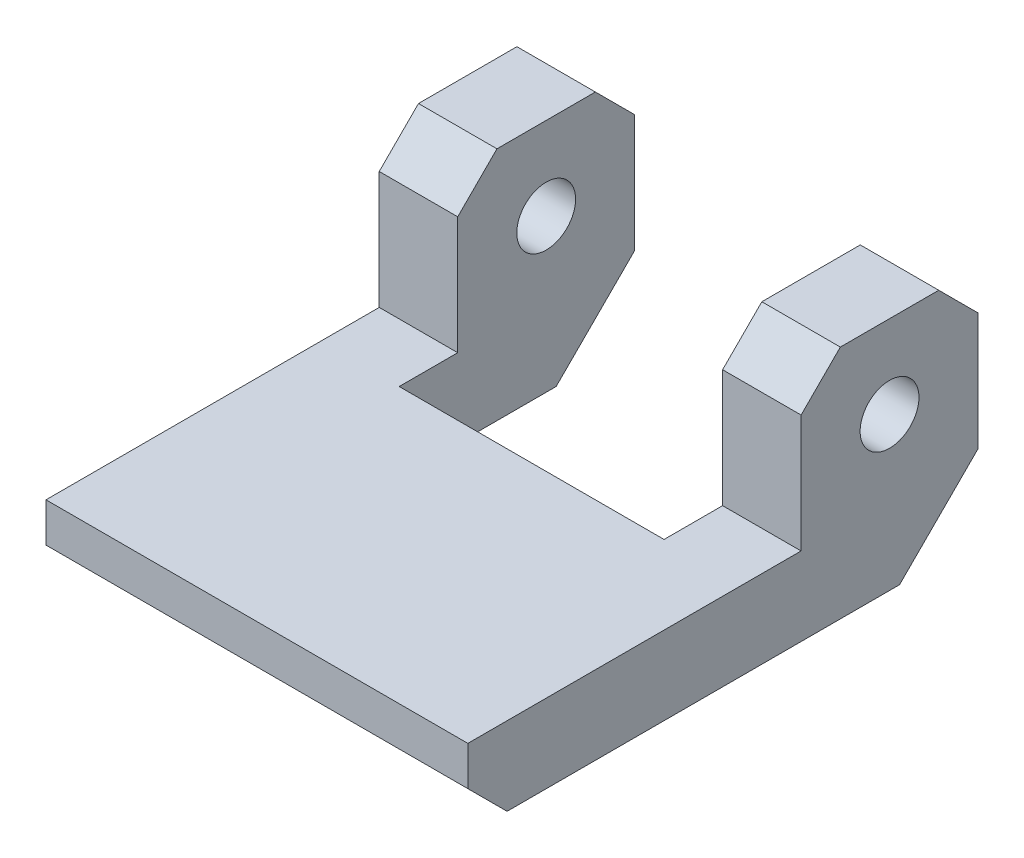
SolidWorks part; units mm, degrees
ref_plane "Спереди" through (0, 0, 0) normal (0, 0, 1) x (1, 0, 0)
ref_plane "Сверху" through (0, 0, 0) normal (0, 1, 0) x (1, 0, 0)
ref_plane "Справа" through (0, 0, 0) normal (1, 0, 0) x (0, 0, -1)
sketch "Эскиз1" plane through (0, 0, 0) normal (0, 1, 0) x (1, 0, 0)
  line L1 (0, 0) -> (21.5, 0)
  line L2 (0, 0) -> (0, -26)
  line L3 (0, -26) -> (21.5, -26)
  line L4 (21.5, 0) -> (21.5, -26)
extrude "Вытянуть1" add sketch "Эскиз1" along normal blind 12
sketch "Эскиз2" plane through (21.5, 0, 0) normal (1, 0, 0) x (0, 0, -1)
  line L0 (4.8026, 4) -> (-2.9217, 4) construction
  line L3 (-31.4385, 13.0177) -> (-9.0163, 13.0177)
  line L4 (-31.4385, 13.0177) -> (-31.4385, 4)
  line L5 (-31.4385, 4) -> (-9.0163, 4)
  line L6 (-9.0163, 13.0177) -> (-9.0163, 4)
  line L7 (-26, 0) -> (0, 0) construction
  dimension "D1" = 4
extrude "Вырез-Вытянуть1" cut sketch "Эскиз2" against normal through all
chamfer "Фаска1" distance 2 angle 45 2 edges at (10.75, 12, 0) (10.75, 12, 9.0163)
chamfer "Фаска2" distance 4 angle 45 1 edges at (10.75, 0, 0)
sketch "Эскиз3" plane through (21.5, 0, 0) normal (1, 0, 0) x (0, 0, -1)
  line L0 (-4.5081, 12) -> (-4.5081, 13.7201) construction
  circle A0 centre (-4.5081, 7.7771) radius 1.5
extrude "Вырез-Вытянуть2" cut sketch "Эскиз3" against normal through all
sketch "Эскиз4" plane through (0, 12, 0) normal (0, 1, 0) x (1, 0, 0)
  line L2 (0, 0) -> (21.5, 0) construction
  line L3 (4, 6.0325) -> (17.5, 6.0325)
  line L4 (4, 6.0325) -> (4, -12)
  line L5 (4, -12) -> (17.5, -12)
  line L6 (17.5, 6.0325) -> (17.5, -12)
  dimension "D1" = 12
extrude "Вырез-Вытянуть3" cut sketch "Эскиз4" against normal through all
chamfer "Фаска3" distance 2 angle 45 1 edges at (10.75, 0, 26)
